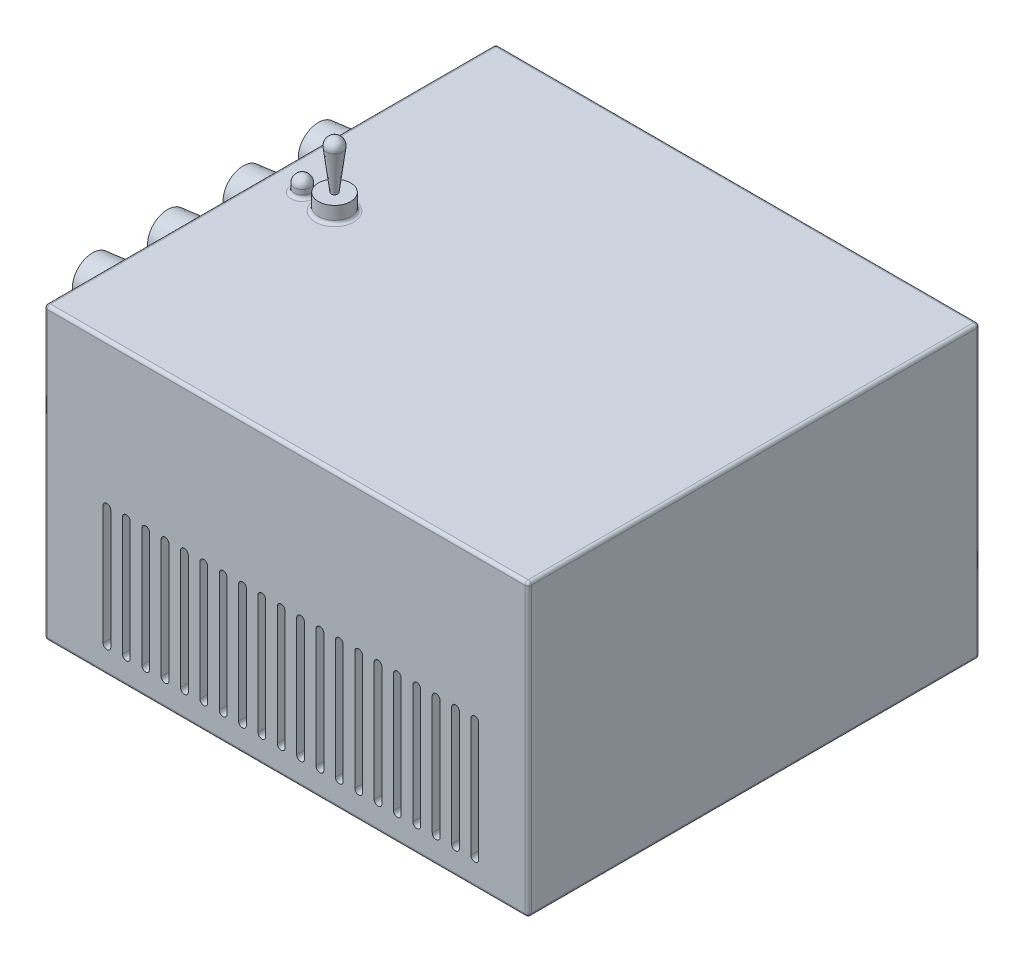
SolidWorks part; units mm, degrees
ref_plane "Front Plane" through (0, 0, 0) normal (0, 0, 1) x (1, 0, 0)
ref_plane "Top Plane" through (0, 0, 0) normal (0, 1, 0) x (1, 0, 0)
ref_plane "Right Plane" through (0, 0, 0) normal (1, 0, 0) x (0, 0, -1)
sketch "Sketch1" plane through (0, 0, 0) normal (0, 0, 1) x (1, 0, 0)
  line L0 (0, 80.0287) -> (0, -78.8793) construction
  line L1 (-129.8851, 0) -> (131.3218, 0) construction
  line L3 (-75, 45) -> (75, 45)
  line L4 (-75, 45) -> (-75, -45)
  line L5 (-75, -45) -> (75, -45)
  line L6 (75, 45) -> (75, -45)
  dimension "D1" = 150
  dimension "D2" = 90
extrude "Boss-Extrude1" add sketch "Sketch1" along normal blind 140
sketch "Sketch2" plane through (-75, 0, 0) normal (-1, 0, 0) x (0, 0, 1)
  line L0 (-14.2259, 25) -> (156.6887, 25) construction
  line L1 (105, 53.4416) -> (105, -52.4565) construction
  line L2 (35, 55.4118) -> (35, -52.4565) construction
  line L3 (0, 45) -> (0, -45) construction
  line L4 (140, 45) -> (140, -45) construction
  line L5 (140, 45) -> (0, 45) construction
  circle A0 centre (35, 25) radius 7.5
  circle A1 centre (105, 25) radius 7.5
  circle A2 centre (58.3, 25) radius 7.5
  circle A3 centre (81.7, 25) radius 7.5
  dimension "D4" = 15
  dimension "D5" = 15
  dimension "D6" = 15
  dimension "D7" = 15
  dimension "D8" = 23.3
  dimension "D9" = 23.3
  dimension "D10" = 70
  dimension "D1" = 35
  dimension "D2" = 35
  dimension "D3" = 20
extrude "Boss-Extrude2" add sketch "Sketch2" along normal blind 20
chamfer "Chamfer1" distance 12 angle 6 4 edges at (-95, 25, 42.5) (-95, 25, 65.8) (-95, 25, 89.2) (-95, 25, 112.5)
sketch "Sketch3" plane through (-95, 0, 0) normal (-1, 0, 0) x (0, 0, 1)
  circle A0 centre (35, 25) radius 4
  circle A1 centre (58.3, 25) radius 4
  circle A2 centre (81.7, 25) radius 4
  circle A3 centre (105, 25) radius 4
  circle A4 centre (35, 25) radius 6.2387 construction
  circle A5 centre (58.3, 25) radius 6.2387 construction
  circle A6 centre (81.7, 25) radius 6.2387 construction
  circle A7 centre (105, 25) radius 6.2387 construction
  dimension "D1" = 8
  dimension "D2" = 8
  dimension "D3" = 8
  dimension "D4" = 8
extrude "Cut-Extrude1" cut sketch "Sketch3" against normal up to surface (20 mm away) up to face at (-75, 25, 50.8)
sketch "Sketch4" plane through (0, 45, 0) normal (0, 1, 0) x (1, 0, 0)
  line L0 (-65, 8.296) -> (-65, -146.3838) construction
  line L1 (-75, -140) -> (-75, 0) construction
  line L2 (-75, -70) -> (75, -70) construction
  line L3 (75, -140) -> (75, 0) construction
  line L4 (-55, 8.296) -> (-55, -146.3838) construction
  circle A0 centre (-65, -70) radius 2.5
  dimension "D3" = 5
  dimension "D1" = 10
  dimension "D2" = 20
extrude "Boss-Extrude3" add sketch "Sketch4" along normal blind 5
fillet "Fillet4" radius 2.5 1 edges at (-67.5, 50, 70)
sketch "Sketch5" plane through (0, 45, 0) normal (0, 1, 0) x (1, 0, 0)
  line L0 (-65, -70) -> (75, -70) construction
  line L1 (75, -140) -> (75, 0) construction
  line L2 (-55, 0) -> (-55, -140) construction
  line L3 (75, 0) -> (-75, 0) construction
  line L4 (75, -140) -> (-75, -140) construction
  line L5 (-75, -140) -> (-75, 0) construction
  circle A0 centre (-55, -70) radius 5
  dimension "D2" = 10
  dimension "D1" = 20
extrude "Boss-Extrude4" add sketch "Sketch5" along normal blind 5
sketch "Sketch6" plane through (0, 50, 0) normal (0, 1, 0) x (1, 0, 0)
  line L0 (-52.25, 0) -> (52.25, 0) construction
  circle A0 centre (-55, -70) radius 2.9334
ref_plane "Plane1" through (0, 0, 70) normal (0, 0, -1) x (-1, 0, 0)
sketch "Sketch8" plane through (0, 0, 70) normal (0, 0, -1) x (-1, 0, 0)
  line L0 (55, 50) -> (55, 64.5169) construction
  line L1 (57.9334, 50) -> (52.0666, 50) construction
  line L2 (54, 50) -> (52.5, 62)
  line L3 (54, 50) -> (55, 50)
  line L4 (55, 50) -> (55, 65)
  arc A0 (52.5, 62) -> (55, 65) centre (55, 62.4583) cw
  dimension "D4" = 15
  dimension "D1" = 1
  dimension "D2" = 2.5
  dimension "D3" = 12
revolve "Revolve6" add sketch "Sketch8" angle 360 about L0
fillet "Fillet5" radius 1 18 edges at (75, -45, 70) (75, 0, 140) (0, -45, 140) (0, -45, 0) (75, 0, 0) (-75, 25, 74.2) (-75, 25, 97.5) (-75, 0, 140) (-75, -45, 70) (-75, 0, 0) (-75, 25, 27.5) (-75, 25, 50.8) (-50, 45, 70) (75, 45, 70) (0, 45, 140) (-75, 45, 70) (0, 45, 0) (-62.5, 45, 70)
sketch "Sketch9" plane through (0, 0, 140) normal (0, 0, 1) x (1, 0, 0)
  line L0 (-55.5206, 0) -> (-55.5206, -36.8184) construction
  line L1 (-54.3227, 0) -> (-54.3227, -36.8184)
  line L2 (-56.7185, 0) -> (-56.7185, -36.8184)
  line L3 (-49.5206, 0) -> (-49.5206, -36.8184) construction
  line L4 (-48.3227, 0) -> (-48.3227, -36.8184)
  line L5 (-50.7185, 0) -> (-50.7185, -36.8184)
  line L6 (-43.5206, 0) -> (-43.5206, -36.8184) construction
  line L7 (-42.3227, 0) -> (-42.3227, -36.8184)
  line L8 (-44.7185, 0) -> (-44.7185, -36.8184)
  line L9 (-37.5206, 0) -> (-37.5206, -36.8184) construction
  line L10 (-36.3227, 0) -> (-36.3227, -36.8184)
  line L11 (-38.7185, 0) -> (-38.7185, -36.8184)
  line L12 (-31.5206, 0) -> (-31.5206, -36.8184) construction
  line L13 (-30.3227, 0) -> (-30.3227, -36.8184)
  line L14 (-32.7185, 0) -> (-32.7185, -36.8184)
  line L15 (-25.5206, 0) -> (-25.5206, -36.8184) construction
  line L16 (-24.3227, 0) -> (-24.3227, -36.8184)
  line L17 (-26.7185, 0) -> (-26.7185, -36.8184)
  line L18 (-19.5206, 0) -> (-19.5206, -36.8184) construction
  line L19 (-18.3227, 0) -> (-18.3227, -36.8184)
  line L20 (-20.7185, 0) -> (-20.7185, -36.8184)
  line L21 (-13.5206, 0) -> (-13.5206, -36.8184) construction
  line L22 (-12.3227, 0) -> (-12.3227, -36.8184)
  line L23 (-14.7185, 0) -> (-14.7185, -36.8184)
  line L24 (-7.5206, 0) -> (-7.5206, -36.8184) construction
  line L25 (-6.3227, 0) -> (-6.3227, -36.8184)
  line L26 (-8.7185, 0) -> (-8.7185, -36.8184)
  line L27 (-1.5206, 0) -> (-1.5206, -36.8184) construction
  line L28 (-0.3227, 0) -> (-0.3227, -36.8184)
  line L29 (-2.7185, 0) -> (-2.7185, -36.8184)
  line L30 (4.4794, 0) -> (4.4794, -36.8184) construction
  line L31 (5.6773, 0) -> (5.6773, -36.8184)
  line L32 (3.2815, 0) -> (3.2815, -36.8184)
  line L33 (10.4794, 0) -> (10.4794, -36.8184) construction
  line L34 (11.6773, 0) -> (11.6773, -36.8184)
  line L35 (9.2815, 0) -> (9.2815, -36.8184)
  line L36 (16.4794, 0) -> (16.4794, -36.8184) construction
  line L37 (17.6773, 0) -> (17.6773, -36.8184)
  line L38 (15.2815, 0) -> (15.2815, -36.8184)
  line L39 (22.4794, 0) -> (22.4794, -36.8184) construction
  line L40 (23.6773, 0) -> (23.6773, -36.8184)
  line L41 (21.2815, 0) -> (21.2815, -36.8184)
  line L42 (28.4794, 0) -> (28.4794, -36.8184) construction
  line L43 (29.6773, 0) -> (29.6773, -36.8184)
  line L44 (27.2815, 0) -> (27.2815, -36.8184)
  line L45 (34.4794, 0) -> (34.4794, -36.8184) construction
  line L46 (35.6773, 0) -> (35.6773, -36.8184)
  line L47 (33.2815, 0) -> (33.2815, -36.8184)
  line L48 (40.4794, 0) -> (40.4794, -36.8184) construction
  line L49 (41.6773, 0) -> (41.6773, -36.8184)
  line L50 (39.2815, 0) -> (39.2815, -36.8184)
  line L51 (46.4794, 0) -> (46.4794, -36.8184) construction
  line L52 (47.6773, 0) -> (47.6773, -36.8184)
  line L53 (45.2815, 0) -> (45.2815, -36.8184)
  line L54 (52.4794, 0) -> (52.4794, -36.8184) construction
  line L55 (53.6773, 0) -> (53.6773, -36.8184)
  line L56 (51.2815, 0) -> (51.2815, -36.8184)
  line L57 (58.4794, 0) -> (58.4794, -36.8184) construction
  line L58 (59.6773, 0) -> (59.6773, -36.8184)
  line L59 (57.2815, 0) -> (57.2815, -36.8184)
  arc A0 (-54.3227, 0) -> (-56.7185, 0) centre (-55.5206, 0) ccw
  arc A1 (-56.7185, -36.8184) -> (-54.3227, -36.8184) centre (-55.5206, -36.8184) ccw
  arc A2 (-48.3227, 0) -> (-50.7185, 0) centre (-49.5206, 0) ccw
  arc A3 (-50.7185, -36.8184) -> (-48.3227, -36.8184) centre (-49.5206, -36.8184) ccw
  arc A4 (-42.3227, 0) -> (-44.7185, 0) centre (-43.5206, 0) ccw
  arc A5 (-44.7185, -36.8184) -> (-42.3227, -36.8184) centre (-43.5206, -36.8184) ccw
  arc A6 (-36.3227, 0) -> (-38.7185, 0) centre (-37.5206, 0) ccw
  arc A7 (-38.7185, -36.8184) -> (-36.3227, -36.8184) centre (-37.5206, -36.8184) ccw
  arc A8 (-30.3227, 0) -> (-32.7185, 0) centre (-31.5206, 0) ccw
  arc A9 (-32.7185, -36.8184) -> (-30.3227, -36.8184) centre (-31.5206, -36.8184) ccw
  arc A10 (-24.3227, 0) -> (-26.7185, 0) centre (-25.5206, 0) ccw
  arc A11 (-26.7185, -36.8184) -> (-24.3227, -36.8184) centre (-25.5206, -36.8184) ccw
  arc A12 (-18.3227, 0) -> (-20.7185, 0) centre (-19.5206, 0) ccw
  arc A13 (-20.7185, -36.8184) -> (-18.3227, -36.8184) centre (-19.5206, -36.8184) ccw
  arc A14 (-12.3227, 0) -> (-14.7185, 0) centre (-13.5206, 0) ccw
  arc A15 (-14.7185, -36.8184) -> (-12.3227, -36.8184) centre (-13.5206, -36.8184) ccw
  arc A16 (-6.3227, 0) -> (-8.7185, 0) centre (-7.5206, 0) ccw
  arc A17 (-8.7185, -36.8184) -> (-6.3227, -36.8184) centre (-7.5206, -36.8184) ccw
  arc A18 (-0.3227, 0) -> (-2.7185, 0) centre (-1.5206, 0) ccw
  arc A19 (-2.7185, -36.8184) -> (-0.3227, -36.8184) centre (-1.5206, -36.8184) ccw
  arc A20 (5.6773, 0) -> (3.2815, 0) centre (4.4794, 0) ccw
  arc A21 (3.2815, -36.8184) -> (5.6773, -36.8184) centre (4.4794, -36.8184) ccw
  arc A22 (11.6773, 0) -> (9.2815, 0) centre (10.4794, 0) ccw
  arc A23 (9.2815, -36.8184) -> (11.6773, -36.8184) centre (10.4794, -36.8184) ccw
  arc A24 (17.6773, 0) -> (15.2815, 0) centre (16.4794, 0) ccw
  arc A25 (15.2815, -36.8184) -> (17.6773, -36.8184) centre (16.4794, -36.8184) ccw
  arc A26 (23.6773, 0) -> (21.2815, 0) centre (22.4794, 0) ccw
  arc A27 (21.2815, -36.8184) -> (23.6773, -36.8184) centre (22.4794, -36.8184) ccw
  arc A28 (29.6773, 0) -> (27.2815, 0) centre (28.4794, 0) ccw
  arc A29 (27.2815, -36.8184) -> (29.6773, -36.8184) centre (28.4794, -36.8184) ccw
  arc A30 (35.6773, 0) -> (33.2815, 0) centre (34.4794, 0) ccw
  arc A31 (33.2815, -36.8184) -> (35.6773, -36.8184) centre (34.4794, -36.8184) ccw
  arc A32 (41.6773, 0) -> (39.2815, 0) centre (40.4794, 0) ccw
  arc A33 (39.2815, -36.8184) -> (41.6773, -36.8184) centre (40.4794, -36.8184) ccw
  arc A34 (47.6773, 0) -> (45.2815, 0) centre (46.4794, 0) ccw
  arc A35 (45.2815, -36.8184) -> (47.6773, -36.8184) centre (46.4794, -36.8184) ccw
  arc A36 (53.6773, 0) -> (51.2815, 0) centre (52.4794, 0) ccw
  arc A37 (51.2815, -36.8184) -> (53.6773, -36.8184) centre (52.4794, -36.8184) ccw
  arc A38 (59.6773, 0) -> (57.2815, 0) centre (58.4794, 0) ccw
  arc A39 (57.2815, -36.8184) -> (59.6773, -36.8184) centre (58.4794, -36.8184) ccw
  point P2 (-55.5206, -18.4092)
  point P10 (-49.5206, -18.4092)
  point P17 (-43.5206, -18.4092)
  point P24 (-37.5206, -18.4092)
  point P31 (-31.5206, -18.4092)
  point P38 (-25.5206, -18.4092)
  point P45 (-19.5206, -18.4092)
  point P52 (-13.5206, -18.4092)
  point P59 (-7.5206, -18.4092)
  point P66 (-1.5206, -18.4092)
  point P73 (4.4794, -18.4092)
  point P80 (10.4794, -18.4092)
  point P87 (16.4794, -18.4092)
  point P94 (22.4794, -18.4092)
  point P101 (28.4794, -18.4092)
  point P108 (34.4794, -18.4092)
  point P115 (40.4794, -18.4092)
  point P122 (46.4794, -18.4092)
  point P129 (52.4794, -18.4092)
  point P136 (58.4794, -18.4092)
  dimension "D1" = 20
extrude "Cut-Extrude2" cut sketch "Sketch9" against normal through all
